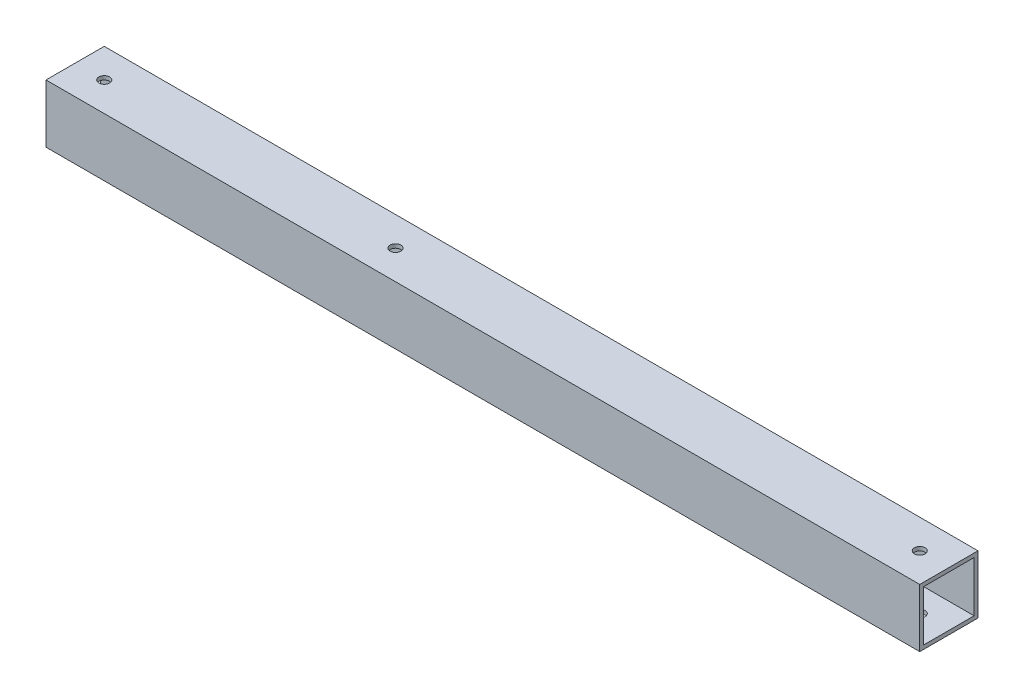
SolidWorks part; units mm, degrees
ref_plane "Front Plane" through (0, 0, 0) normal (0, 0, 1) x (1, 0, 0)
ref_plane "Top Plane" through (0, 0, 0) normal (0, 1, 0) x (1, 0, 0)
ref_plane "Right Plane" through (0, 0, 0) normal (1, 0, 0) x (0, 0, -1)
sketch "Sketch1" plane through (0, 0, 0) normal (1, 0, 0) x (0, 0, -1)
  line L1 (15, 15) -> (-15, 15)
  line L2 (15, 15) -> (15, -15)
  line L3 (15, -15) -> (-15, -15)
  line L4 (-15, 15) -> (-15, -15)
  line L5 (15, 15) -> (-15, -15) construction
  line L6 (15, -15) -> (-15, 15) construction
  line L7 (-13, 13) -> (13, 13)
  line L8 (-13, 13) -> (-13, -13)
  line L9 (-13, -13) -> (13, -13)
  line L10 (13, 13) -> (13, -13)
  line L11 (-13, 13) -> (13, -13) construction
  line L12 (-13, -13) -> (13, 13) construction
  point P0 (0, 0)
  point P5 (0, 0)
  dimension "D1" = 30
  dimension "D2" = 30
  dimension "D3" = 2
extrude "Boss-Extrude1" add sketch "Sketch1" along normal mid plane 450
sketch "Sketch2" plane through (0, 0, 0) normal (0, 1, 0) x (1, 0, 0)
  line L0 (225, 15) -> (225, -15) construction
  circle A0 centre (210, 0) radius 2.75
  dimension "D1" = 5.5
  dimension "D2" = 15
extrude "Cut-Extrude1" cut sketch "Sketch2" against normal through all both and the other way through all
mirror "Mirror1" about plane through (0, 0, 0) normal (1, 0, 0) of "Cut-Extrude1"
sketch "Sketch3" plane through (0, 0, 0) normal (0, 1, 0) x (1, 0, 0)
  line L0 (-210, 0) -> (-60, 0) construction
  circle A0 centre (-60, 0) radius 2.75
  dimension "D2" = 5.5
  dimension "D1" = 150
extrude "Cut-Extrude2" cut sketch "Sketch3" against normal through all both and the other way through all
equation "\"D2@Sketch1\"=\"w\""
equation "\"D1@Sketch1\"=\"w\""
equation "\"t\"= 2"
equation "\"w\"= 30"
equation "\"D3@Sketch1\"=\"t\""
equation "\"D2@Sketch2\"=\"w\"/2"
